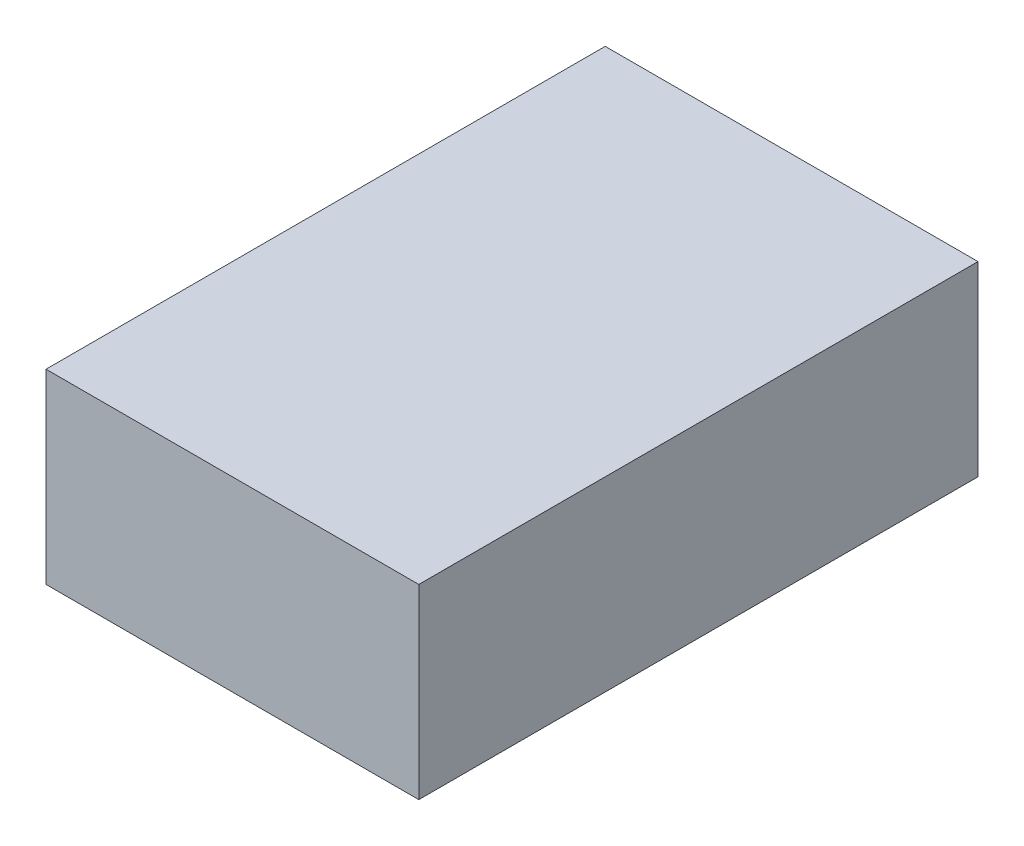
SolidWorks part; units mm, degrees
ref_plane "Plan de face" through (0, 0, 0) normal (0, 0, 1) x (1, 0, 0)
ref_plane "Plan de dessus" through (0, 0, 0) normal (0, 1, 0) x (1, 0, 0)
ref_plane "Plan de droite" through (0, 0, 0) normal (1, 0, 0) x (0, 0, -1)
sketch "Esquisse2" plane through (0, 0, 0) normal (0, 0, 1) x (1, 0, 0)
  line L1 (-2, -1) -> (2, -1)
  line L2 (-2, -1) -> (-2, 1)
  line L3 (-2, 1) -> (2, 1)
  line L4 (2, -1) -> (2, 1)
  line L5 (-2, -1) -> (2, 1) construction
  line L6 (-2, 1) -> (2, -1) construction
  point P0 (0, 0)
  dimension "D1" = 4
  dimension "D2" = 2
extrude "Boss.-Extru.1" add sketch "Esquisse2" along normal blind 6
